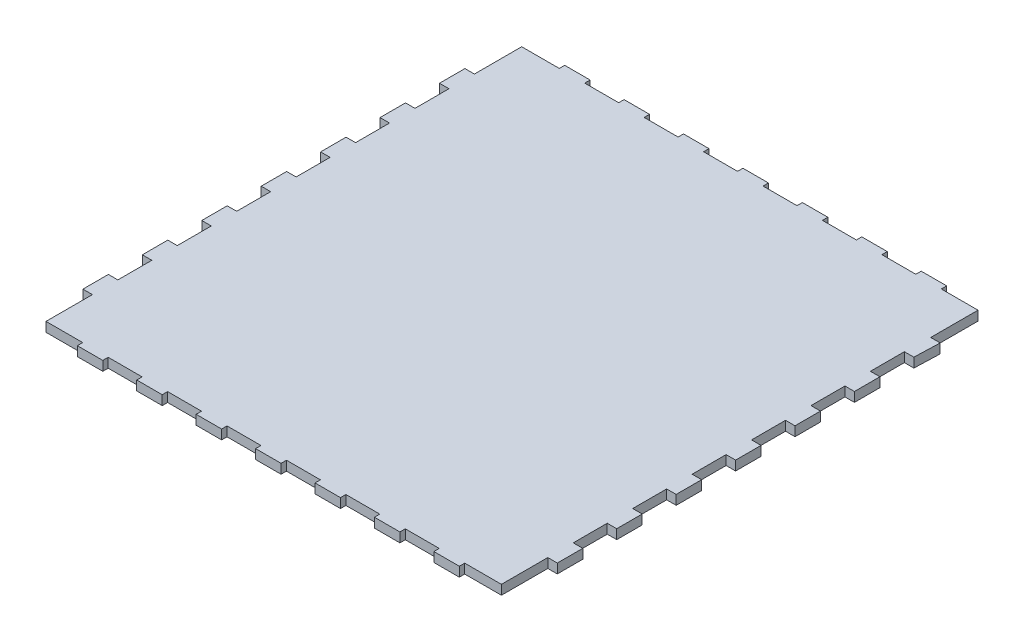
SolidWorks part; units mm, degrees
ref_plane "Front Plane" through (0, 0, 0) normal (0, 0, 1) x (1, 0, 0)
ref_plane "Top Plane" through (0, 0, 0) normal (0, 1, 0) x (1, 0, 0)
ref_plane "Right Plane" through (0, 0, 0) normal (1, 0, 0) x (0, 0, -1)
sketch "Sketch1" plane through (0, 0, 0) normal (0, 1, 0) x (1, 0, 0)
  line L0 (-83.6549, -164.9939) -> (-83.6549, -161.8189) construction
  line L1 (126.341, -164.9939) -> (141.341, -164.9939)
  line L2 (-110.8549, 90.5) -> (-110.8549, 75.5)
  line L3 (-83.6549, -164.9939) -> (-68.6549, -164.9939)
  line L5 (-110.8549, -161.8189) -> (-83.6549, -161.8189) construction
  line L7 (-68.6549, -164.9939) -> (-68.6549, -161.8189) construction
  line L8 (-68.6549, -161.8189) -> (-48.6509, -161.8189) construction
  line L9 (-48.6509, -164.9939) -> (-48.6509, -161.8189) construction
  line L10 (-33.6549, -164.9939) -> (-33.6549, -161.8189) construction
  line L11 (-33.6549, -161.8189) -> (-13.6549, -161.8189) construction
  line L12 (-13.6549, -164.9939) -> (-13.6549, -161.8189) construction
  line L13 (1.3491, -164.9939) -> (1.3491, -161.8189) construction
  line L14 (1.3491, -161.8189) -> (21.3451, -161.8189) construction
  line L15 (21.3451, -164.9939) -> (21.3451, -161.8189) construction
  line L16 (36.3411, -164.9939) -> (36.3411, -161.8189) construction
  line L17 (36.3411, -161.8189) -> (56.3411, -161.8189) construction
  line L18 (56.3411, -164.9939) -> (56.3411, -161.8189) construction
  line L19 (71.3411, -164.9939) -> (71.3411, -161.8189) construction
  line L20 (71.3411, -161.8189) -> (91.3451, -161.8189) construction
  line L21 (91.3451, -164.9939) -> (91.3451, -161.8189) construction
  line L22 (106.3451, -164.9939) -> (106.3451, -161.8189) construction
  line L23 (106.3451, -161.8189) -> (126.341, -161.8189) construction
  line L24 (126.341, -164.9939) -> (126.341, -161.8189) construction
  line L25 (141.341, -164.9939) -> (141.341, -161.8189) construction
  line L26 (141.341, -161.8189) -> (169.0531, -161.8189) construction
  line L27 (-83.6549, -164.9939) -> (-83.6549, -161.8189)
  line L28 (-105.2669, -161.8189) -> (-83.6549, -161.8189)
  line L29 (-105.2669, -134.5) -> (-105.2669, -161.8189)
  line L30 (-68.6549, -164.9939) -> (-68.6549, -161.8189)
  line L31 (-68.6549, -161.8189) -> (-48.6509, -161.8189)
  line L32 (-48.6509, -164.9939) -> (-48.6509, -161.8189)
  line L33 (-33.6549, -164.9939) -> (-33.6549, -161.8189)
  line L34 (-33.6549, -161.8189) -> (-13.6549, -161.8189)
  line L35 (-13.6549, -164.9939) -> (-13.6549, -161.8189)
  line L36 (1.3491, -164.9939) -> (1.3491, -161.8189)
  line L37 (1.3491, -161.8189) -> (21.3451, -161.8189)
  line L38 (21.3451, -164.9939) -> (21.3451, -161.8189)
  line L39 (36.3411, -164.9939) -> (36.3411, -161.8189)
  line L40 (36.3411, -161.8189) -> (56.3411, -161.8189)
  line L41 (56.3411, -164.9939) -> (56.3411, -161.8189)
  line L42 (71.3411, -164.9939) -> (71.3411, -161.8189)
  line L43 (71.3411, -161.8189) -> (91.3451, -161.8189)
  line L44 (91.3451, -164.9939) -> (91.3451, -161.8189)
  line L45 (106.3451, -164.9939) -> (106.3451, -161.8189)
  line L46 (106.3451, -161.8189) -> (126.341, -161.8189)
  line L47 (126.341, -164.9939) -> (126.341, -161.8189)
  line L48 (141.341, -164.9939) -> (141.341, -161.8189)
  line L49 (141.341, -161.8189) -> (162.9571, -161.8189)
  line L50 (-110.8549, -134.5) -> (-110.8549, 137.3353) construction
  line L51 (-105.2669, 90.5) -> (-105.2669, 118.3503)
  line L52 (163.4651, 90.5) -> (163.4651, 118.3503)
  line L53 (162.9571, -134.5) -> (162.9571, -161.8189)
  line L71 (91.3451, -164.9939) -> (106.3451, -164.9939)
  line L72 (56.3411, -164.9939) -> (71.3411, -164.9939)
  line L73 (21.3451, -164.9939) -> (36.3411, -164.9939)
  line L74 (-48.6509, -164.9939) -> (-33.6549, -164.9939)
  line L75 (-13.6549, -164.9939) -> (1.3491, -164.9939)
  line L76 (-83.1469, 118.3503) -> (-83.1469, 121.5253) construction
  line L77 (-68.1469, 118.3503) -> (-68.1469, 121.5253) construction
  line L78 (-48.1469, 118.3503) -> (-48.1469, 121.5253) construction
  line L79 (-33.1469, 118.3503) -> (-33.1469, 121.5253) construction
  line L80 (-13.1469, 118.3503) -> (-13.1469, 121.5253) construction
  line L82 (-105.2669, 118.3503) -> (-83.1469, 118.3503) construction
  line L83 (-83.1469, 121.5253) -> (-68.1469, 121.5253) construction
  line L84 (-68.1469, 118.3503) -> (-48.1469, 118.3503) construction
  line L85 (-48.1469, 121.5253) -> (-33.1469, 121.5253) construction
  line L86 (-33.1469, 118.3503) -> (-13.1469, 118.3503) construction
  line L87 (-13.1469, 121.5253) -> (1.8531, 121.5253) construction
  line L88 (1.8531, 118.3503) -> (1.8531, 121.5253) construction
  line L89 (1.8531, 118.3503) -> (21.8531, 118.3503) construction
  line L90 (21.8531, 118.3503) -> (21.8531, 121.5253) construction
  line L91 (21.8531, 121.5253) -> (36.8531, 121.5253) construction
  line L92 (36.8531, 118.3503) -> (36.8531, 121.5253) construction
  line L93 (36.8531, 118.3503) -> (56.8531, 118.3503) construction
  line L94 (56.8531, 118.3503) -> (56.8531, 121.5253) construction
  line L95 (56.8531, 121.5253) -> (71.8531, 121.5253) construction
  line L96 (71.8531, 118.3503) -> (71.8531, 121.5253) construction
  line L97 (71.8531, 118.3503) -> (91.8531, 118.3503) construction
  line L98 (91.8531, 118.3503) -> (91.8531, 121.5253) construction
  line L99 (91.8531, 121.5253) -> (106.8531, 121.5253) construction
  line L100 (106.8531, 118.3503) -> (106.8531, 121.5253) construction
  line L101 (106.8531, 118.3503) -> (126.8531, 118.3503) construction
  line L102 (126.8531, 118.3503) -> (126.8531, 121.5253) construction
  line L103 (126.8531, 121.5253) -> (141.8531, 121.5253) construction
  line L104 (141.8531, 118.3503) -> (141.8531, 121.5253) construction
  line L105 (141.8531, 118.3503) -> (163.4651, 118.3503) construction
  line L135 (-83.1469, 118.3503) -> (-83.1469, 121.5253)
  line L136 (-68.1469, 118.3503) -> (-68.1469, 121.5253)
  line L137 (-48.1469, 118.3503) -> (-48.1469, 121.5253)
  line L138 (-33.1469, 118.3503) -> (-33.1469, 121.5253)
  line L139 (-13.1469, 118.3503) -> (-13.1469, 121.5253)
  line L141 (-105.2669, 118.3503) -> (-83.1469, 118.3503)
  line L142 (-83.1469, 121.5253) -> (-68.1469, 121.5253)
  line L143 (-68.1469, 118.3503) -> (-48.1469, 118.3503)
  line L144 (-48.1469, 121.5253) -> (-33.1469, 121.5253)
  line L145 (-33.1469, 118.3503) -> (-13.1469, 118.3503)
  line L146 (-13.1469, 121.5253) -> (1.8531, 121.5253)
  line L147 (1.8531, 118.3503) -> (1.8531, 121.5253)
  line L148 (1.8531, 118.3503) -> (21.8531, 118.3503)
  line L149 (21.8531, 118.3503) -> (21.8531, 121.5253)
  line L150 (21.8531, 121.5253) -> (36.8531, 121.5253)
  line L151 (36.8531, 118.3503) -> (36.8531, 121.5253)
  line L152 (36.8531, 118.3503) -> (56.8531, 118.3503)
  line L153 (56.8531, 118.3503) -> (56.8531, 121.5253)
  line L154 (56.8531, 121.5253) -> (71.8531, 121.5253)
  line L155 (71.8531, 118.3503) -> (71.8531, 121.5253)
  line L156 (71.8531, 118.3503) -> (91.8531, 118.3503)
  line L157 (91.8531, 118.3503) -> (91.8531, 121.5253)
  line L158 (91.8531, 121.5253) -> (106.8531, 121.5253)
  line L159 (106.8531, 118.3503) -> (106.8531, 121.5253)
  line L160 (106.8531, 118.3503) -> (126.8531, 118.3503)
  line L161 (126.8531, 118.3503) -> (126.8531, 121.5253)
  line L162 (126.8531, 121.5253) -> (141.8531, 121.5253)
  line L163 (141.8531, 118.3503) -> (141.8531, 121.5253)
  line L164 (141.8531, 118.3503) -> (163.4651, 118.3503)
  line L166 (169.0531, 90.5) -> (163.4651, 90.5)
  line L167 (168.5451, 75.5) -> (169.0531, 90.5)
  line L168 (168.5451, 75.5) -> (162.9571, 75.5)
  line L169 (162.9571, 75.5) -> (162.9571, 55.5)
  line L170 (168.5451, 55.5) -> (162.9571, 55.5)
  line L171 (168.5451, 40.5) -> (168.5451, 55.5)
  line L172 (168.5451, 40.5) -> (162.9571, 40.5)
  line L173 (162.9571, 40.5) -> (162.9571, 20.5)
  line L174 (168.5451, 20.5) -> (162.9571, 20.5)
  line L175 (168.5451, 5.5) -> (168.5451, 20.5)
  line L176 (168.5451, 5.5) -> (162.9571, 5.5)
  line L177 (162.9571, 5.5) -> (162.9571, -14.5)
  line L178 (168.5451, -14.5) -> (162.9571, -14.5)
  line L179 (168.5451, -29.5) -> (168.5451, -14.5)
  line L180 (168.5451, -29.5) -> (162.9571, -29.5)
  line L181 (162.9571, -29.5) -> (162.9571, -49.5)
  line L182 (168.5451, -49.5) -> (162.9571, -49.5)
  line L183 (168.5451, -49.5) -> (168.5451, -64.5)
  line L184 (168.5451, -64.5) -> (162.9571, -64.5)
  line L185 (162.9571, -64.5) -> (162.9571, -84.5)
  line L186 (168.5451, -84.5) -> (162.9571, -84.5)
  line L187 (168.5451, -84.5) -> (168.5451, -99.5)
  line L188 (168.5451, -99.5) -> (162.9571, -99.5)
  line L189 (162.9571, -99.5) -> (162.9571, -119.5)
  line L190 (168.5451, -119.5) -> (162.9571, -119.5)
  line L191 (168.5451, -119.5) -> (168.5451, -134.5)
  line L192 (168.5451, -134.5) -> (162.9571, -134.5)
  line L213 (-105.2669, -134.5) -> (-110.8549, -134.5)
  line L214 (-105.2669, -119.5) -> (-110.8549, -119.5)
  line L215 (-105.2669, -99.5) -> (-105.2669, -119.5)
  line L216 (-105.2669, -99.5) -> (-110.8549, -99.5)
  line L217 (-105.2669, -84.5) -> (-110.8549, -84.5)
  line L218 (-105.2669, -64.5) -> (-105.2669, -84.5)
  line L219 (-105.2669, -64.5) -> (-110.8549, -64.5)
  line L220 (-105.2669, -49.5) -> (-110.8549, -49.5)
  line L221 (-105.2669, -29.5) -> (-105.2669, -49.5)
  line L222 (-105.2669, -29.5) -> (-110.8549, -29.5)
  line L223 (-105.2669, -14.5) -> (-110.8549, -14.5)
  line L224 (-105.2669, 5.5) -> (-105.2669, -14.5)
  line L225 (-105.2669, 5.5) -> (-110.8549, 5.5)
  line L226 (-105.2669, 20.5) -> (-110.8549, 20.5)
  line L227 (-105.2669, 40.5) -> (-105.2669, 20.5)
  line L228 (-105.2669, 40.5) -> (-110.8549, 40.5)
  line L229 (-105.2669, 55.5) -> (-110.8549, 55.5)
  line L230 (-105.2669, 75.5) -> (-105.2669, 55.5)
  line L231 (-105.2669, 75.5) -> (-110.8549, 75.5)
  line L232 (-105.2669, 90.5) -> (-110.8549, 90.5)
  line L233 (-110.8549, 55.5) -> (-110.8549, 40.5)
  line L234 (-110.8549, 20.5) -> (-110.8549, 5.5)
  line L235 (-110.8549, -14.5) -> (-110.8549, -29.5)
  line L236 (-110.8549, -119.5) -> (-110.8549, -134.5)
  line L237 (-110.8549, -84.5) -> (-110.8549, -99.5)
  line L238 (-110.8549, -49.5) -> (-110.8549, -64.5)
  dimension "D1" = 5.588
  dimension "D2" = 5.588
  dimension "D3" = 5.588
  dimension "D4" = 5.588
  dimension "D5" = 5.588
  dimension "D6" = 5.588
  dimension "D7" = 5.588
  dimension "D9" = 5.588
  dimension "D10" = 5.588
  dimension "D11" = 5.588
  dimension "D13" = 5.588
  dimension "D14" = 5.588
  dimension "D15" = 5.588
  dimension "D8" = 5.588
  dimension "D12" = 5.588
  dimension "D16" = 5.588
  dimension "D17" = 5.588
  dimension "D18" = 5.588
  dimension "D19" = 5.588
  dimension "D20" = 5.588
  dimension "D21" = 5.588
  dimension "D22" = 5.588
extrude "Boss-Extrude1" add sketch "Sketch1" along normal blind 5.588
